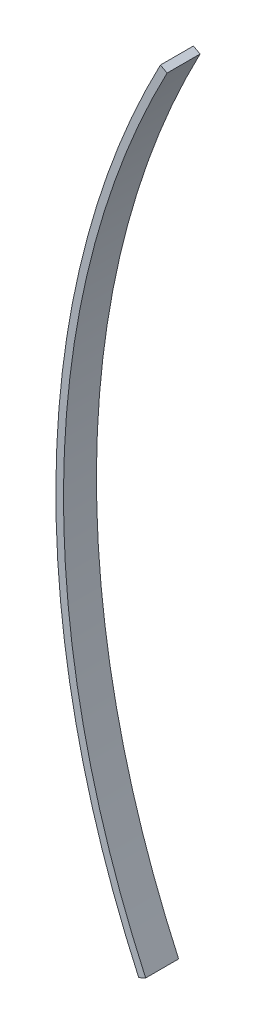
SolidWorks part; units mm, degrees
ref_plane "Front Plane" through (0, 0, 0) normal (0, 0, 1) x (1, 0, 0)
ref_plane "Top Plane" through (0, 0, 0) normal (0, 1, 0) x (1, 0, 0)
ref_plane "Right Plane" through (0, 0, 0) normal (1, 0, 0) x (0, 0, -1)
sketch "Sketch1" plane through (0, 0, 0) normal (0, 0, 1) x (1, 0, 0)
  arc B0 (9.4233, 171.953) -> (5.1903, 15.2885) centre (166.2366, 89.3266) ccw
  arc B1 (13.0798, 10.4448) -> (150.8717, 85.1111) centre (6.2297, 187.5624) ccw
  arc B2 (151.1218, 94.3656) -> (17.5629, 176.3637) centre (1.1585, -0.1256) ccw
  circle B3 centre (57.875, 92.2544) radius 58.5
  circle B4 centre (57.875, 92.2544) radius 55
  circle B5 centre (57.875, 92.2544) radius 59.5
  circle B6 centre (57.875, 92.2544) radius 63
sketch_block_instance "Block1-1"
sketch_block "Block1"
extrude "Extrude-Thin1" add sketch "Sketch1" against normal blind 6.5 thin contours B0
